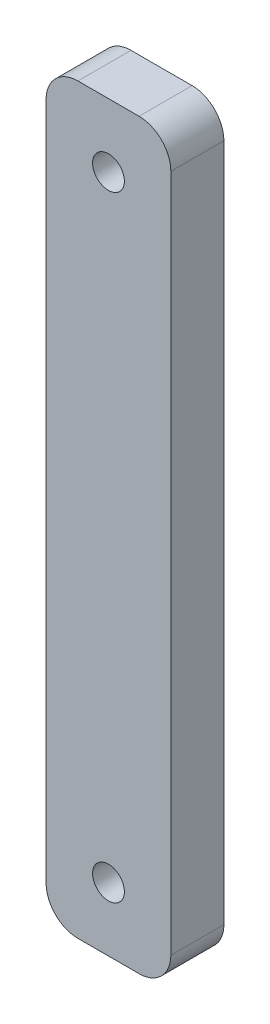
SolidWorks part; units mm, degrees
ref_plane "Front Plane" through (0, 0, 0) normal (0, 0, 1) x (1, 0, 0)
ref_plane "Top Plane" through (0, 0, 0) normal (0, 1, 0) x (1, 0, 0)
ref_plane "Right Plane" through (0, 0, 0) normal (1, 0, 0) x (0, 0, -1)
sketch "Sketch1" plane through (0, 0, 0) normal (0, 0, 1) x (1, 0, 0)
  line L0 (0, 0) -> (0, -29) construction
  line L1 (2.88, -35) -> (-2.88, -35)
  line L2 (5.88, -32) -> (5.88, 32)
  line L3 (2.88, 35) -> (-2.88, 35)
  line L4 (-5.88, -32) -> (-5.88, 32)
  line L5 (5.88, -35) -> (-5.88, 35) construction
  line L6 (5.88, 35) -> (-5.88, -35) construction
  line L7 (0, 0) -> (0, 29) construction
  arc A0 (-2.88, 35) -> (-5.88, 32) centre (-2.88, 32) ccw
  arc A1 (5.88, 32) -> (2.88, 35) centre (2.88, 32) ccw
  arc A2 (2.88, -35) -> (5.88, -32) centre (2.88, -32) ccw
  arc A3 (-2.88, -35) -> (-5.88, -32) centre (-2.88, -32) cw
  circle A4 centre (0, -29) radius 1.5
  circle A5 centre (0, 29) radius 1.5
  point P0 (0, 0)
  dimension "D3" = 3
  dimension "D4" = 3
  dimension "D5" = 3
  dimension "D6" = 3
  dimension "D8" = 29
  dimension "D1" = 70
  dimension "D2" = 11.76
  dimension "D7" = 29
extrude "Boss-Extrude1" add sketch "Sketch1" along normal blind 5
